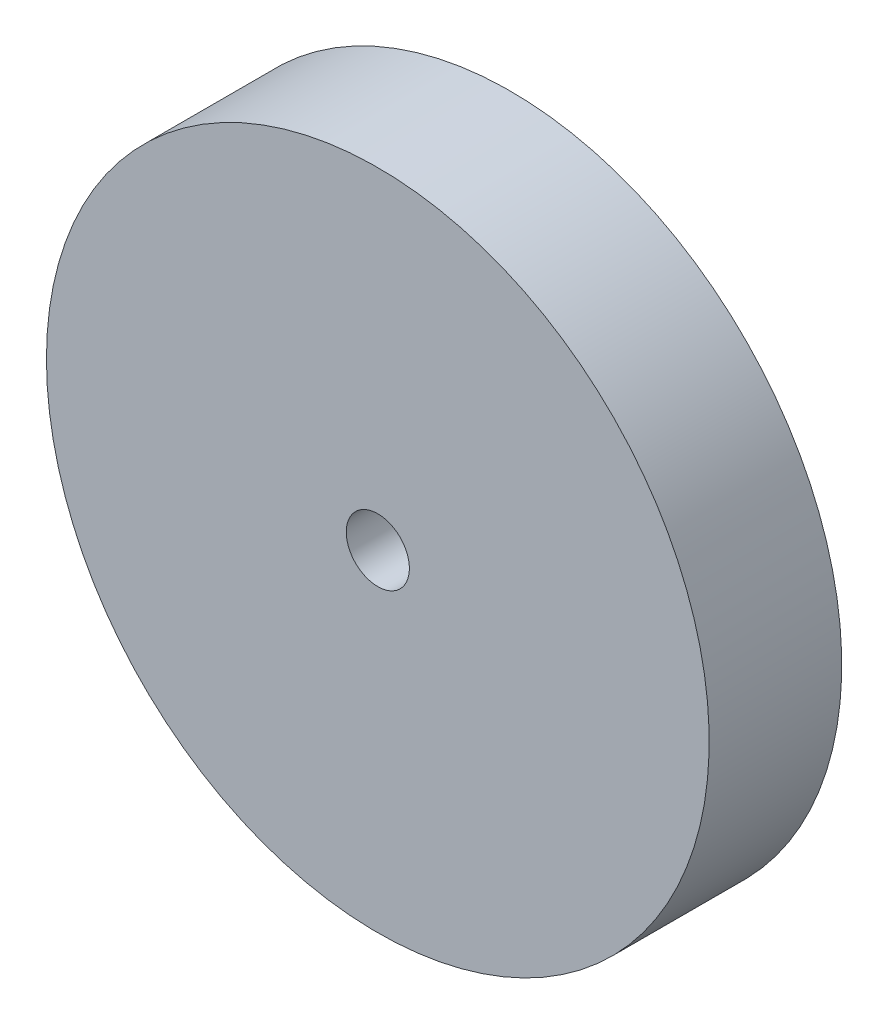
SolidWorks part; units mm, degrees
ref_plane "Front Plane" through (0, 0, 0) normal (0, 0, 1) x (1, 0, 0)
ref_plane "Top Plane" through (0, 0, 0) normal (0, 1, 0) x (1, 0, 0)
ref_plane "Right Plane" through (0, 0, 0) normal (1, 0, 0) x (0, 0, -1)
sketch "Sketch1" plane through (0, 0, 0) normal (0, 0, 1) x (1, 0, 0)
  circle A0 centre (0, 0) radius 52.5
  circle A1 centre (0, 0) radius 5
  dimension "D1" = 105
  dimension "D2" = 10
extrude "Boss-Extrude1" add sketch "Sketch1" along normal blind 21
